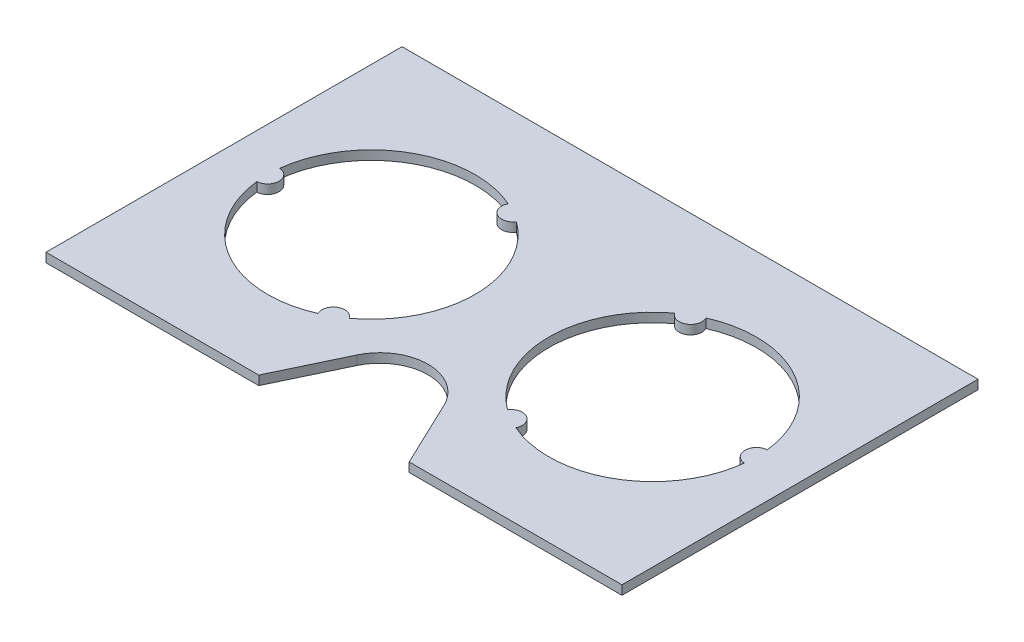
SolidWorks part; units mm, degrees
ref_plane "前视基准面" through (0, 0, 0) normal (0, 0, 1) x (1, 0, 0)
ref_plane "上视基准面" through (0, 0, 0) normal (0, 1, 0) x (1, 0, 0)
ref_plane "右视基准面" through (0, 0, 0) normal (1, 0, 0) x (0, 0, -1)
sketch "草图1" plane through (0, 0, 0) normal (0, 1, 0) x (1, 0, 0)
  line L0 (9.51, -38.85) -> (32.16, -38.85) construction
  line L1 (0, 0) -> (125.7, 0)
  line L2 (0, 0) -> (0, -77.7)
  line L3 (0, -77.7) -> (125.7, -77.7) construction
  line L4 (125.7, 0) -> (125.7, -77.7)
  line L5 (32.16, -38.85) -> (43.485, -19.2345) construction
  line L6 (62.85, 0) -> (62.85, -77.7) construction
  line L7 (93.54, -38.85) -> (82.215, -19.2345) construction
  line L8 (116.19, -38.85) -> (93.54, -38.85) construction
  line L9 (0, -77.7) -> (46.435, -77.7)
  line L10 (46.435, -77.7) -> (79.265, -77.7) construction
  line L11 (79.265, -77.7) -> (125.7, -77.7)
  line L12 (46.435, -77.7) -> (53.35, -63.1783)
  line L13 (72.35, -63.1783) -> (79.265, -77.7)
  line L14 (51.6636, -57.18) -> (76.7828, -57.18) construction
  circle A0 centre (32.16, -38.85) radius 22.65 construction
  circle A1 centre (93.54, -38.85) radius 22.65 construction
  arc A2 (9.648, -36.3538) -> (41.2543, -18.1059) centre (32.16, -38.85) cw
  arc A3 (45.5778, -20.6021) -> (45.5778, -57.0979) centre (32.16, -38.85) cw
  arc A4 (41.2543, -59.5941) -> (9.648, -41.3462) centre (32.16, -38.85) cw
  arc A5 (9.648, -36.3538) -> (9.648, -41.3462) centre (9.51, -38.85) cw
  arc A6 (41.2543, -18.1059) -> (45.5778, -20.6021) centre (43.485, -19.2345) ccw
  arc A7 (45.5778, -57.0979) -> (41.2543, -59.5941) centre (43.485, -58.4655) ccw
  arc A8 (80.1222, -57.0979) -> (84.4457, -59.5941) centre (82.215, -58.4655) cw
  arc A9 (84.4457, -18.1059) -> (80.1222, -20.6021) centre (82.215, -19.2345) cw
  arc A10 (116.052, -36.3538) -> (116.052, -41.3462) centre (116.19, -38.85) ccw
  arc A11 (84.4457, -59.5941) -> (116.052, -41.3462) centre (93.54, -38.85) ccw
  arc A12 (80.1222, -20.6021) -> (80.1222, -57.0979) centre (93.54, -38.85) ccw
  arc A13 (116.052, -36.3538) -> (84.4457, -18.1059) centre (93.54, -38.85) ccw
  arc A14 (53.35, -63.1783) -> (72.35, -63.1783) centre (62.85, -67.7021) cw
  point P9 (0, -38.85)
  point P10 (9.51, -38.85)
  point P11 (43.485, -19.2345)
  point P12 (43.485, -58.4655)
  point P35 (62.85, -77.7)
  dimension "D5" = 45.3
  dimension "D6" = 20.52
  dimension "D8" = 2.5
  dimension "D9" = 2.5
  dimension "D10" = 2.5
  dimension "D11" = 19
  dimension "D1" = 125.7
  dimension "D2" = 77.7
  dimension "D3" = 32.16
  dimension "D4" = 32.83
  dimension "D7" = 120
extrude "凸台-拉伸1" add sketch "草图1" along normal blind 2
